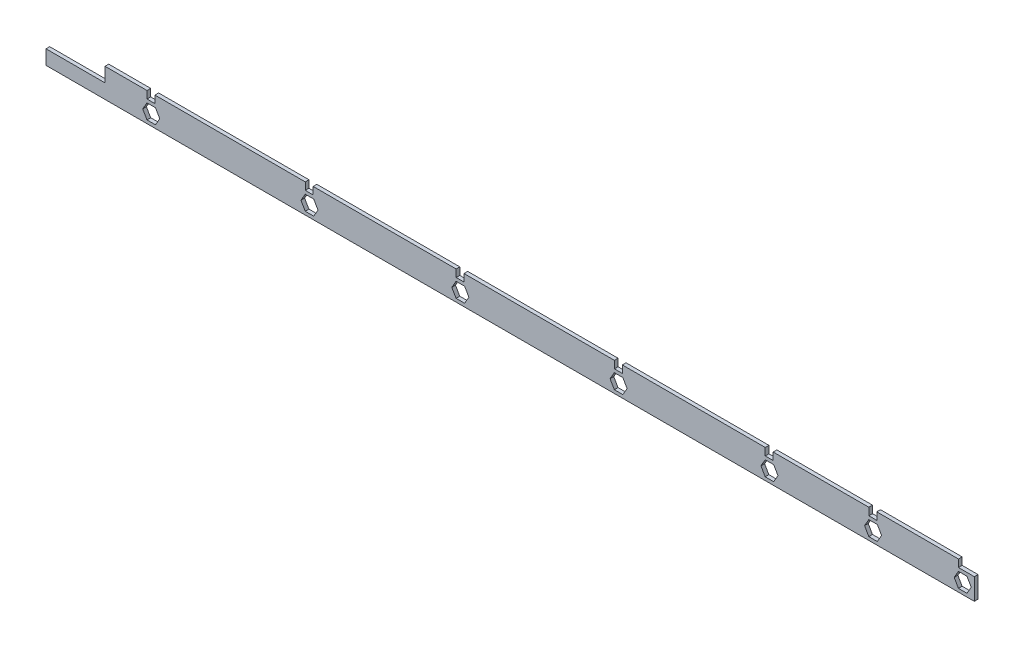
SolidWorks part; units mm, degrees
ref_plane "Front Plane" through (0, 0, 0) normal (0, 0, 1) x (1, 0, 0)
ref_plane "Top Plane" through (0, 0, 0) normal (0, 1, 0) x (1, 0, 0)
ref_plane "Right Plane" through (0, 0, 0) normal (1, 0, 0) x (0, 0, -1)
sketch "Sketch1" plane through (0, 0, 0) normal (0, 0, 1) x (1, 0, 0)
  line L0 (6838.8727, 2682.0269) -> (6838.8727, 2685.2019)
  line L1 (6489.8704, 2685.2019) -> (6489.8704, 2682.0269)
  line L2 (6493.274, 2685.2019) -> (6493.274, 2682.0269)
  line L3 (6557.9297, 2685.2019) -> (6557.9297, 2682.0269)
  line L4 (6561.3333, 2685.2019) -> (6561.3333, 2682.0269)
  line L5 (6622.814, 2685.2019) -> (6622.814, 2682.0269)
  line L6 (6626.2176, 2685.2019) -> (6626.2176, 2682.0269)
  line L7 (6690.8733, 2685.2019) -> (6690.8733, 2682.0269)
  line L8 (6694.2769, 2685.2019) -> (6694.2769, 2682.0269)
  line L9 (6755.7576, 2685.2019) -> (6755.7576, 2682.0269)
  line L10 (6759.1612, 2685.2019) -> (6759.1612, 2682.0269)
  line L11 (6800.3238, 2685.2019) -> (6800.3238, 2682.0269)
  line L12 (6803.7274, 2685.2019) -> (6803.7274, 2682.0269)
  line L13 (6845.6799, 2682.0269) -> (6838.8727, 2682.0269)
  line L14 (6803.7274, 2682.0269) -> (6800.3238, 2682.0269)
  line L15 (6759.1612, 2682.0269) -> (6755.7576, 2682.0269)
  line L16 (6694.2769, 2682.0269) -> (6690.8733, 2682.0269)
  line L17 (6626.2176, 2682.0269) -> (6622.814, 2682.0269)
  line L18 (6561.3333, 2682.0269) -> (6557.9297, 2682.0269)
  line L19 (6493.274, 2682.0269) -> (6489.8704, 2682.0269)
  line L20 (6838.8727, 2685.2019) -> (6803.7274, 2685.2019)
  line L21 (6800.3238, 2685.2019) -> (6759.1612, 2685.2019)
  line L22 (6755.7576, 2685.2019) -> (6694.2769, 2685.2019)
  line L23 (6690.8733, 2685.2019) -> (6626.2176, 2685.2019)
  line L24 (6622.814, 2685.2019) -> (6561.3333, 2685.2019)
  line L25 (6557.9297, 2685.2019) -> (6493.274, 2685.2019)
  line L26 (6489.8704, 2685.2019) -> (6471.83, 2685.2019)
  line L27 (6845.6799, 2672.8321) -> (6446.43, 2672.8321)
  line L28 (6493.5196, 2674.2545) -> (6495.3527, 2677.4295)
  line L29 (6495.3527, 2677.4295) -> (6493.5196, 2680.6045)
  line L30 (6493.5196, 2680.6045) -> (6489.8534, 2680.6045)
  line L31 (6489.8534, 2680.6045) -> (6488.0203, 2677.4295)
  line L32 (6488.0203, 2677.4295) -> (6489.8534, 2674.2545)
  line L33 (6489.8534, 2674.2545) -> (6493.5196, 2674.2545)
  line L34 (6561.5789, 2674.2545) -> (6563.412, 2677.4295)
  line L35 (6563.412, 2677.4295) -> (6561.5789, 2680.6045)
  line L36 (6561.5789, 2680.6045) -> (6557.9127, 2680.6045)
  line L37 (6557.9127, 2680.6045) -> (6556.0796, 2677.4295)
  line L38 (6556.0796, 2677.4295) -> (6557.9127, 2674.2545)
  line L39 (6557.9127, 2674.2545) -> (6561.5789, 2674.2545)
  line L40 (6626.4632, 2674.2545) -> (6628.2963, 2677.4295)
  line L41 (6628.2963, 2677.4295) -> (6626.4632, 2680.6045)
  line L42 (6626.4632, 2680.6045) -> (6622.797, 2680.6045)
  line L43 (6622.797, 2680.6045) -> (6620.9639, 2677.4295)
  line L44 (6620.9639, 2677.4295) -> (6622.797, 2674.2545)
  line L45 (6622.797, 2674.2545) -> (6626.4632, 2674.2545)
  line L46 (6694.5225, 2674.2545) -> (6696.3556, 2677.4295)
  line L47 (6696.3556, 2677.4295) -> (6694.5225, 2680.6045)
  line L48 (6694.5225, 2680.6045) -> (6690.8563, 2680.6045)
  line L49 (6690.8563, 2680.6045) -> (6689.0232, 2677.4295)
  line L50 (6689.0232, 2677.4295) -> (6690.8563, 2674.2545)
  line L51 (6690.8563, 2674.2545) -> (6694.5225, 2674.2545)
  line L52 (6759.4068, 2674.2545) -> (6761.2399, 2677.4295)
  line L53 (6761.2399, 2677.4295) -> (6759.4068, 2680.6045)
  line L54 (6759.4068, 2680.6045) -> (6755.7406, 2680.6045)
  line L55 (6755.7406, 2680.6045) -> (6753.9075, 2677.4295)
  line L56 (6753.9075, 2677.4295) -> (6755.7406, 2674.2545)
  line L57 (6755.7406, 2674.2545) -> (6759.4068, 2674.2545)
  line L58 (6803.973, 2674.2545) -> (6805.8061, 2677.4295)
  line L59 (6805.8061, 2677.4295) -> (6803.973, 2680.6045)
  line L60 (6803.973, 2680.6045) -> (6800.3069, 2680.6045)
  line L61 (6800.3069, 2680.6045) -> (6798.4738, 2677.4295)
  line L62 (6798.4738, 2677.4295) -> (6800.3069, 2674.2545)
  line L63 (6800.3069, 2674.2545) -> (6803.973, 2674.2545)
  line L64 (6842.5219, 2674.2545) -> (6844.355, 2677.4295)
  line L65 (6844.355, 2677.4295) -> (6842.5219, 2680.6045)
  line L66 (6842.5219, 2680.6045) -> (6838.8558, 2680.6045)
  line L67 (6838.8558, 2680.6045) -> (6837.0227, 2677.4295)
  line L68 (6837.0227, 2677.4295) -> (6838.8558, 2674.2545)
  line L69 (6838.8558, 2674.2545) -> (6842.5219, 2674.2545)
  line L70 (6845.6799, 2672.8321) -> (6845.6799, 2682.0269)
  line L71 (6446.43, 2679.017) -> (6446.43, 2672.8321)
  line L72 (6471.83, 2685.2019) -> (6471.83, 2679.017)
  line L73 (6446.43, 2679.017) -> (6471.83, 2679.017)
extrude "Boss-Extrude1" add sketch "Sketch1" along normal blind 1.5875
